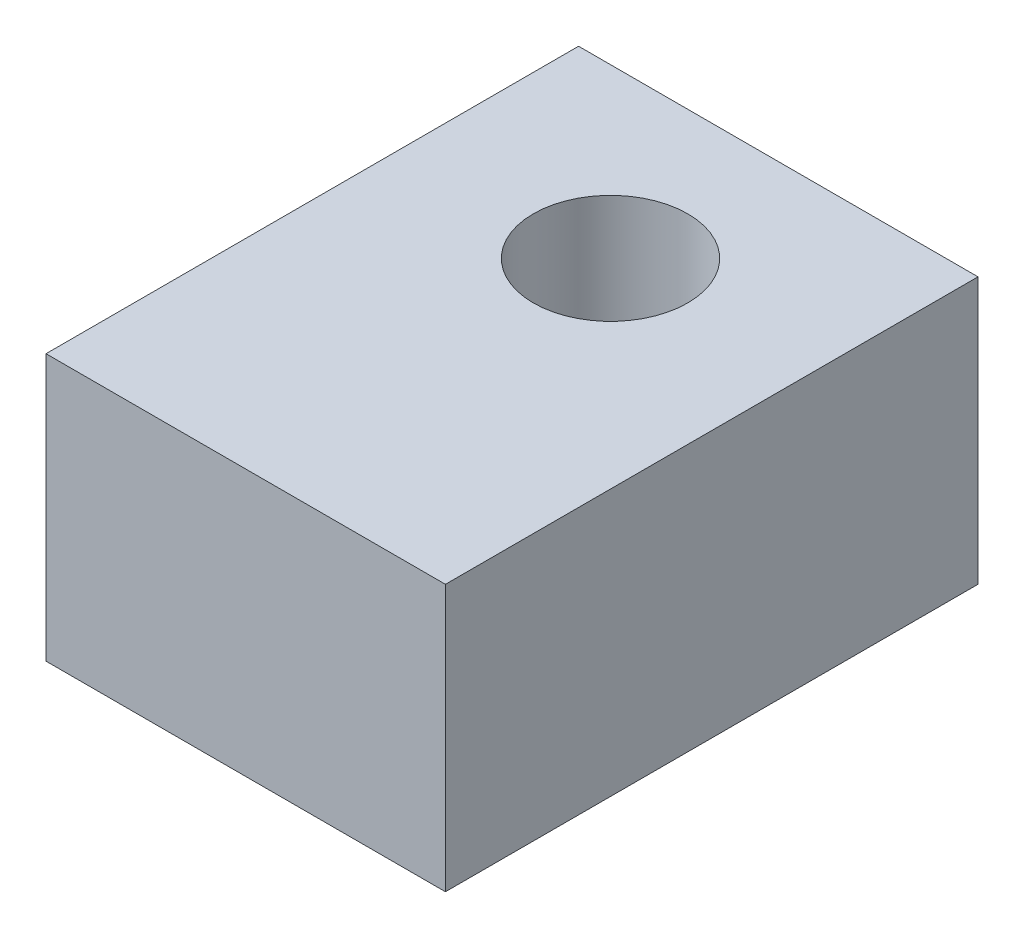
SolidWorks part; units mm, degrees
ref_plane "Front Plane" through (0, 0, 0) normal (1, 0, 0) x (0, 1, 0)
ref_plane "Top Plane" through (0, 0, 0) normal (0, 0, 1) x (0, 1, 0)
ref_plane "Right Plane" through (0, 0, 0) normal (0, 1, 0) x (-1, 0, 0)
sketch "Sketch1" plane through (0, 0, 0) normal (0, 0, 1) x (0, 1, 0)
  line L1 (0, 0) -> (10, 0)
  line L2 (0, 0) -> (0, 15)
  line L3 (0, 15) -> (10, 15)
  line L4 (10, 0) -> (10, 15)
  dimension "D1" = 10
  dimension "D2" = 15
extrude "Boss-Extrude1" add sketch "Sketch1" along normal blind 20
sketch "Sketch3" plane through (0, 10, 0) normal (0, 1, 0) x (1, 0, 0)
  line L0 (0, 0) -> (-15, 0) construction
  circle A0 centre (-7.5, -6.3) radius 2.9
  dimension "D1" = 5.8
  dimension "D2" = 6.3
extrude "Cut-Extrude1" cut sketch "Sketch3" against normal through all
